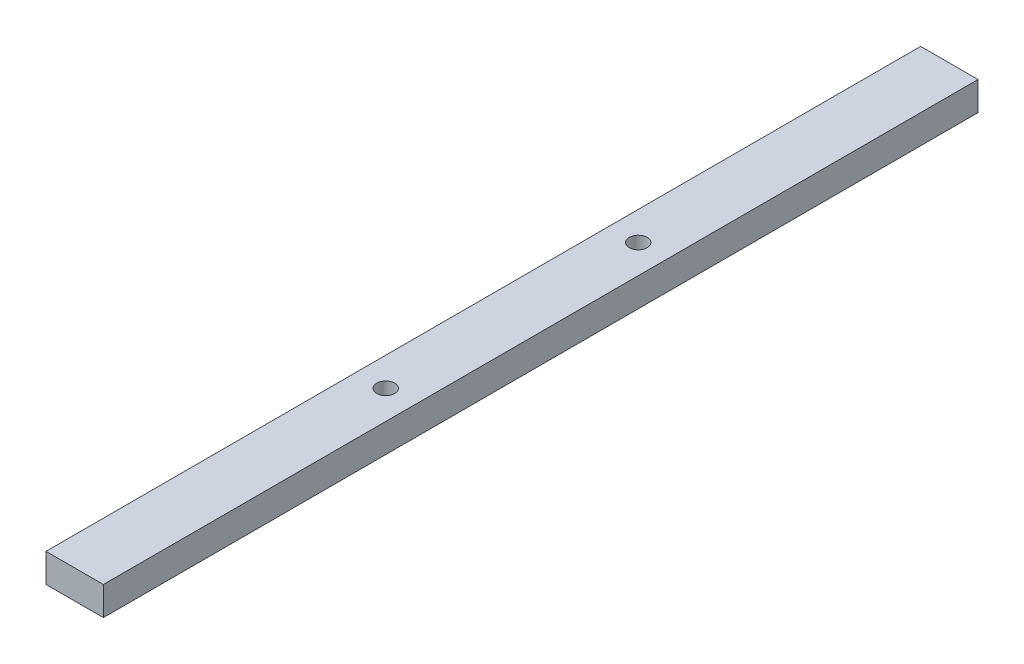
SolidWorks part; units mm, degrees
ref_plane "Front Plane" through (0, 0, 0) normal (0, 0, 1) x (1, 0, 0)
ref_plane "Top Plane" through (0, 0, 0) normal (0, 1, 0) x (1, 0, 0)
ref_plane "Right Plane" through (0, 0, 0) normal (1, 0, 0) x (0, 0, -1)
sketch "Sketch1" plane through (0, 0, 0) normal (0, 0, 1) x (1, 0, 0)
  line L0 (-10, 0) -> (10, 0) construction
  line L1 (0, -5) -> (0, 5) construction
  line L5 (-10, 5) -> (10, 5) construction
  line L7 (-10, 5) -> (-10, -5) construction
  line L8 (10, -5) -> (10, 5) construction
  line L13 (-10, -5) -> (10, -5) construction
  point P0 (0, 0)
  point P4 (0, 0)
  point P9 (0, 0)
  point P22 (0, 5)
  dimension "Thickness" = 10
  dimension "D1" = 20
sketch "Sketch2" plane through (0, 0, 0) normal (0, 1, 0) x (0, 0, -1)
  line L0 (152.4, 0) -> (-152.4, 0) construction
  line L2 (-152.4, 10) -> (152.4, 10) construction
  line L3 (-152.4, 10) -> (-152.4, -10) construction
  line L4 (-152.4, -10) -> (152.4, -10) construction
  line L5 (152.4, 10) -> (152.4, -10) construction
  line L6 (-152.4, 10) -> (152.4, -10) construction
  line L7 (-152.4, -10) -> (152.4, 10) construction
  point P4 (0, 0)
  point P7 (0, 0)
  point P12 (-129.4, 10)
  point P13 (129.4, 10)
  dimension "Length" = 304.8
  dimension "Width" = 20
  dimension "D1" = 23
  dimension "D2" = 23
sketch "Sketch3" plane through (0, 0, 0) normal (0, 0, 1) x (1, 0, 0)
  line L3 (-10, 5) -> (10, 5)
  line L17 (10, 5) -> (10, -5)
  line L18 (10, -5) -> (-10, -5)
  line L19 (-10, -5) -> (-10, 5)
extrude "Boss-Extrude1" add sketch "Sketch3" along normal mid plane 304.8
sketch "Sketch4" plane through (0, 0, 0) normal (0, 1, 0) x (1, 0, 0)
  line L0 (0, 152.4) -> (0, -152.4) construction
  line L1 (10, 152.4) -> (-10, 152.4) construction
  line L2 (10, -152.4) -> (-10, -152.4) construction
  line L3 (10, 0) -> (-10, 0) construction
  line L4 (10, -152.4) -> (10, 152.4) construction
  line L5 (-10, -152.4) -> (-10, 152.4) construction
  circle A0 centre (0, -44) radius 3.125
  circle A1 centre (0, 44) radius 3.125
  dimension "D1" = 6.25
  dimension "D2" = 44
extrude "Cut-Extrude1" cut sketch "Sketch4" along normal mid plane 10
equation "\"D1@Boss-Extrude1\" = \"Length@Sketch2\""
equation "\"D1@Sketch1\"=\"Width@Sketch2\""
equation "\"D1@Sketch2\"=\"Width@Sketch2\"*1.15"
equation "\"D2@Sketch2\"=\"D1@Sketch2\""
